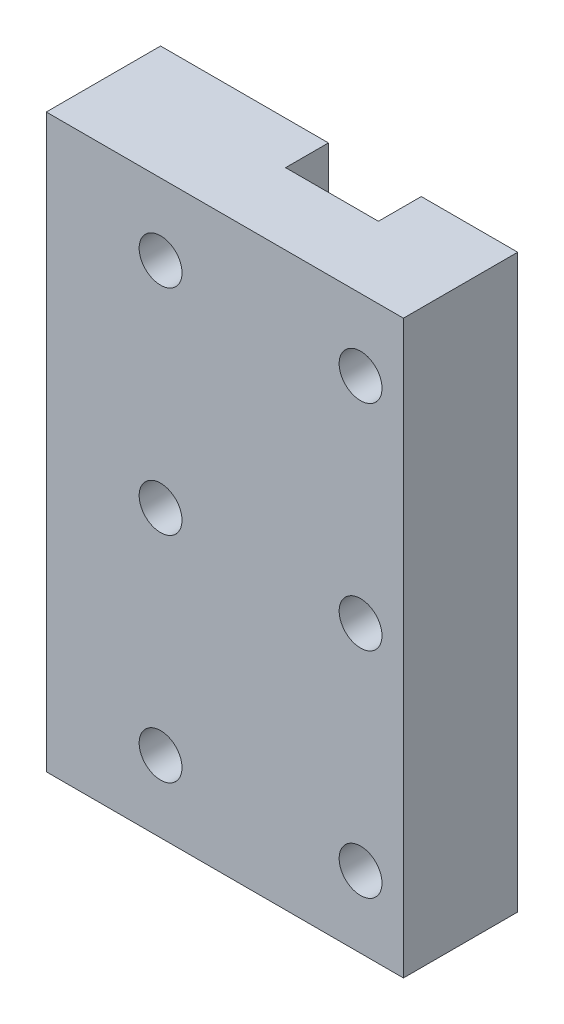
SolidWorks part; units mm, degrees
ref_plane "Front Plane" through (0, 0, 0) normal (0, 0, 1) x (1, 0, 0)
ref_plane "Top Plane" through (0, 0, 0) normal (0, 1, 0) x (1, 0, 0)
ref_plane "Right Plane" through (0, 0, 0) normal (1, 0, 0) x (0, 0, -1)
sketch "Sketch1" plane through (0, 0, 0) normal (0, 0, 1) x (1, 0, 0)
  line L1 (12.5, -20) -> (-12.5, -20)
  line L2 (12.5, -20) -> (12.5, 20)
  line L3 (12.5, 20) -> (-12.5, 20)
  line L4 (-12.5, -20) -> (-12.5, 20)
  line L5 (12.5, -20) -> (-12.5, 20) construction
  line L6 (12.5, 20) -> (-12.5, -20) construction
  circle A0 centre (-4.5, 15) radius 1.5
  circle A1 centre (9.5, 15) radius 1.5
  circle A2 centre (-4.5, 0) radius 1.5
  circle A3 centre (9.5, 0) radius 1.5
  circle A4 centre (-4.5, -15) radius 1.5
  circle A5 centre (9.5, -15) radius 1.5
  point P0 (0, 0)
  dimension "D3" = 14
  dimension "D4" = 3
  dimension "D5" = 3
  dimension "D1" = 40
  dimension "D2" = 25
  dimension "D6" = 5
  dimension "D7" = 3
extrude "Boss-Extrude1" add sketch "Sketch1" along normal blind 8
sketch "Sketch2" plane through (0, 0, 0) normal (0, 0, -1) x (-1, 0, 0)
  line L6 (-12.5, 20) -> (12.5, 20) construction
  line L7 (12.5, -20) -> (-12.5, -20) construction
  line L8 (-5.75, 20) -> (0.75, 20)
  line L9 (-5.75, 20) -> (-5.75, -20)
  line L10 (-5.75, -20) -> (0.75, -20)
  line L11 (0.75, 20) -> (0.75, -20)
  point P8 (-2.5, 20)
  dimension "D1" = 10
  dimension "D2" = 6.5
extrude "Cut-Extrude1" cut sketch "Sketch2" against normal blind 3
sketch "Sketch3" plane through (-0.75, 0, 0) normal (1, 0, 0) x (0, 0, -1)
  line L0 (-3, -20) -> (-3, 20) construction
  line L1 (-3, -20) -> (-3, 20) construction
  line L2 (-3, 19.5) -> (-3, 18.5)
  arc A0 (-3, 19.5) -> (-3, 18.5) centre (-3, 19) ccw
  dimension "D1" = 1
  dimension "D2" = 1
extrude "Cut-Extrude2" cut sketch "Sketch3" along normal up to surface (6.5 mm away) up to face at (5.75, 0, 1.5)
pattern_linear "LPattern1" count 23 spacing 1.923 along (0, -1, 0) of "Cut-Extrude2"
